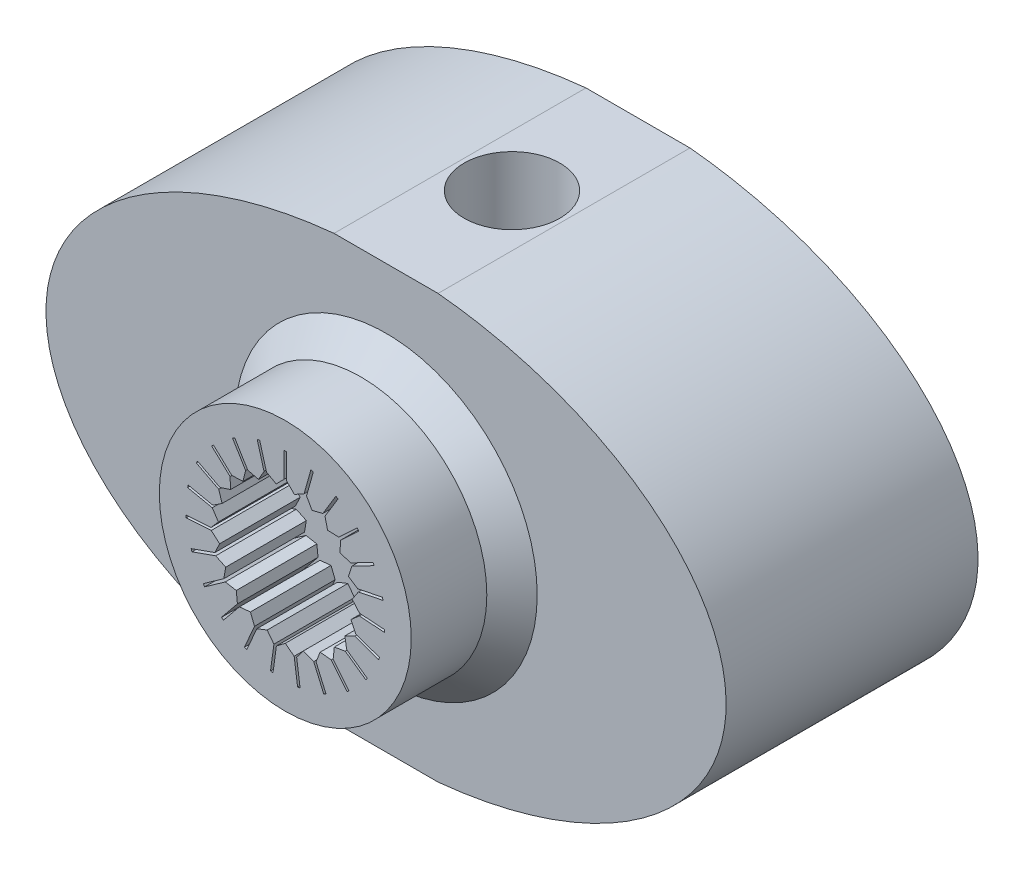
SolidWorks part; units mm, degrees
ref_plane "正面" through (0, 0, 0) normal (0, 0, 1) x (1, 0, 0)
ref_plane "平面" through (0, 0, 0) normal (0, 1, 0) x (1, 0, 0)
ref_plane "右側面" through (0, 0, 0) normal (1, 0, 0) x (0, 0, -1)
sketch "ｽｹｯﾁ1" plane through (0, 0, 0) normal (0, 0, 1) x (1, 0, 0)
  ellipse E0 centre (0, 0) end of major axis (-13.5, 0) minor radius 8.5
  dimension "D1" = 13.5
  dimension "D2" = 8.5
extrude "ﾎﾞｽ - 押し出し1" add sketch "ｽｹｯﾁ1" along normal blind 10
sketch "ｽｹｯﾁ2" plane through (0, 0, 0) normal (0, 1, 0) x (1, 0, 0)
  line L1 (2.5, -13.2881) -> (-2.5, -13.2881)
  line L2 (2.5, -13.2881) -> (2.5, 3.6993)
  line L3 (2.5, 3.6993) -> (-2.5, 3.6993)
  line L4 (-2.5, -13.2881) -> (-2.5, 3.6993)
  line L5 (2.5, -13.2881) -> (-2.5, 3.6993) construction
  line L6 (2.5, 3.6993) -> (-2.5, -13.2881) construction
  point P0 (0, -4.7944)
  dimension "D1" = 5
extrude "ｶｯﾄ - 押し出し2" cut sketch "ｽｹｯﾁ2" against normal blind 10 from offset 18.4
mirror "ﾐﾗｰ1" about plane through (0, 0, 0) normal (0, 1, 0) of "ｶｯﾄ - 押し出し2"
sketch "ｽｹｯﾁ3" plane through (0, 8.4, 0) normal (0, 1, 0) x (1, 0, 0)
  line L0 (2.0647, 0) -> (-2.0647, 0) construction
  line L1 (-2.0647, 0) -> (-2.0647, -10) construction
  circle A0 centre (0, -5) radius 1.9
  point P4 (0, 0)
  point P7 (-2.0647, -5)
  dimension "D1" = 3.8
extrude "ｶｯﾄ - 押し出し3" cut sketch "ｽｹｯﾁ3" against normal through all both and the other way through all
sketch "ｽｹｯﾁ6" plane through (0, 0, 10) normal (0, 0, 1) x (1, 0, 0)
  circle A0 centre (0, 0) radius 5
  dimension "D1" = 10
extrude "ﾎﾞｽ - 押し出し3" add sketch "ｽｹｯﾁ6" along normal blind 4
sketch "ｽｹｯﾁ5" plane through (0, 0, 14) normal (0, 0, 1) x (1, 0, 0)
  line L0 (-0.3625, 2.6375) -> (0, 3) construction
  line L1 (0, 3) -> (0.3625, 2.6375) construction
  line L2 (-0.3625, 2.6375) -> (0, 0) construction
  line L3 (0, 0) -> (0.3625, 2.6375) construction
  line L4 (0, 3) -> (0, 0) construction
  line L5 (-0.05, 2.95) -> (-0.05, 3.95)
  line L6 (-0.05, 3.95) -> (0.05, 3.95)
  line L7 (0.05, 3.95) -> (0.05, 2.95)
  line L8 (-0.05, 2.95) -> (0.05, 2.95) construction
  line L9 (-0.3625, 2.6375) -> (-0.05, 2.95)
  line L10 (-0.05, 2.95) -> (0.05, 2.95) construction
  line L11 (0.3625, 2.6375) -> (0.05, 2.95)
  line L12 (0.3625, 2.6375) -> (0.7478, 2.8541)
  line L13 (0.7478, 2.8541) -> (1.0176, 3.817)
  line L14 (1.1138, 3.79) -> (0.844, 2.8271)
  line L15 (1.0607, 2.4419) -> (0.844, 2.8271)
  line L16 (1.0176, 3.817) -> (1.1138, 3.79)
  line L17 (1.0607, 2.4419) -> (1.4901, 2.5465)
  line L18 (1.4901, 2.5465) -> (2.0096, 3.4009)
  line L19 (2.0951, 3.349) -> (1.5755, 2.4946)
  line L20 (1.6801, 2.0652) -> (1.5755, 2.4946)
  line L21 (2.0096, 3.4009) -> (2.0951, 3.349)
  line L22 (1.6801, 2.0652) -> (2.1218, 2.0501)
  line L23 (2.1218, 2.0501) -> (2.8527, 2.7326)
  line L24 (2.9209, 2.6595) -> (2.1901, 1.977)
  line L25 (2.175, 1.5353) -> (2.1901, 1.977)
  line L26 (2.8527, 2.7326) -> (2.9209, 2.6595)
  line L27 (2.175, 1.5353) -> (2.5963, 1.4016)
  line L28 (2.5963, 1.4016) -> (3.4841, 1.8617)
  line L29 (3.5301, 1.7729) -> (2.6423, 1.3128)
  line L30 (2.5086, 0.8915) -> (2.6423, 1.3128)
  line L31 (3.4841, 1.8617) -> (3.5301, 1.7729)
  line L32 (2.5086, 0.8915) -> (2.8781, 0.6491)
  line L33 (2.8781, 0.6491) -> (3.8572, 0.8526)
  line L34 (3.8776, 0.7547) -> (2.8985, 0.5512)
  line L35 (2.6561, 0.1817) -> (2.8985, 0.5512)
  line L36 (3.8572, 0.8526) -> (3.8776, 0.7547)
  line L37 (2.6561, 0.1817) -> (2.9465, -0.1514)
  line L38 (2.9465, -0.1514) -> (3.9442, -0.2197)
  line L39 (3.9374, -0.3194) -> (2.9397, -0.2512)
  line L40 (2.6066, -0.5417) -> (2.9397, -0.2512)
  line L41 (3.9442, -0.2197) -> (3.9374, -0.3194)
  line L42 (2.6066, -0.5417) -> (2.7964, -0.9408)
  line L43 (2.7964, -0.9408) -> (3.7387, -1.2757)
  line L44 (3.7052, -1.3699) -> (2.7629, -1.035)
  line L45 (2.3638, -1.2248) -> (2.7629, -1.035)
  line L46 (3.7387, -1.2757) -> (3.7052, -1.3699)
  line L47 (2.3638, -1.2248) -> (2.4389, -1.6604)
  line L48 (2.4389, -1.6604) -> (3.2559, -2.237)
  line L49 (3.1982, -2.3187) -> (2.3812, -1.7421)
  line L50 (1.9457, -1.8171) -> (2.3812, -1.7421)
  line L51 (3.2559, -2.237) -> (3.1982, -2.3187)
  line L52 (1.9457, -1.8171) -> (1.9005, -2.2568)
  line L53 (1.9005, -2.2568) -> (2.5316, -3.0325)
  line L54 (2.454, -3.0956) -> (1.8229, -2.3199)
  line L55 (1.3833, -2.2747) -> (1.8229, -2.3199)
  line L56 (2.5316, -3.0325) -> (2.454, -3.0956)
  line L57 (1.3833, -2.2747) -> (1.2211, -2.6859)
  line L58 (1.2211, -2.6859) -> (1.6195, -3.6031)
  line L59 (1.5278, -3.6429) -> (1.1294, -2.7257)
  line L60 (0.7183, -2.5636) -> (1.1294, -2.7257)
  line L61 (1.6195, -3.6031) -> (1.5278, -3.6429)
  line L62 (0.7183, -2.5636) -> (0.4512, -2.9157)
  line L63 (0.4512, -2.9157) -> (0.5874, -3.9064)
  line L64 (0.4883, -3.92) -> (0.3522, -2.9293)
  line L65 (0, -2.6623) -> (0.3522, -2.9293)
  line L66 (0.5874, -3.9064) -> (0.4883, -3.92)
  line L67 (0, -2.6623) -> (-0.3522, -2.9293)
  line L68 (-0.3522, -2.9293) -> (-0.4883, -3.92)
  line L69 (-0.5874, -3.9064) -> (-0.4512, -2.9157)
  line L70 (-0.7183, -2.5636) -> (-0.4512, -2.9157)
  line L71 (-0.4883, -3.92) -> (-0.5874, -3.9064)
  line L72 (-0.7183, -2.5636) -> (-1.1294, -2.7257)
  line L73 (-1.1294, -2.7257) -> (-1.5278, -3.6429)
  line L74 (-1.6195, -3.6031) -> (-1.2211, -2.6859)
  line L75 (-1.3833, -2.2747) -> (-1.2211, -2.6859)
  line L76 (-1.5278, -3.6429) -> (-1.6195, -3.6031)
  line L77 (-1.3833, -2.2747) -> (-1.8229, -2.3199)
  line L78 (-1.8229, -2.3199) -> (-2.454, -3.0956)
  line L79 (-2.5316, -3.0325) -> (-1.9005, -2.2568)
  line L80 (-1.9457, -1.8171) -> (-1.9005, -2.2568)
  line L81 (-2.454, -3.0956) -> (-2.5316, -3.0325)
  line L82 (-1.9457, -1.8171) -> (-2.3812, -1.7421)
  line L83 (-2.3812, -1.7421) -> (-3.1982, -2.3187)
  line L84 (-3.2559, -2.237) -> (-2.4389, -1.6604)
  line L85 (-2.3638, -1.2248) -> (-2.4389, -1.6604)
  line L86 (-3.1982, -2.3187) -> (-3.2559, -2.237)
  line L87 (-2.3638, -1.2248) -> (-2.7629, -1.035)
  line L88 (-2.7629, -1.035) -> (-3.7052, -1.3699)
  line L89 (-3.7387, -1.2757) -> (-2.7964, -0.9408)
  line L90 (-2.6066, -0.5417) -> (-2.7964, -0.9408)
  line L91 (-3.7052, -1.3699) -> (-3.7387, -1.2757)
  line L92 (-2.6066, -0.5417) -> (-2.9397, -0.2512)
  line L93 (-2.9397, -0.2512) -> (-3.9374, -0.3194)
  line L94 (-3.9442, -0.2197) -> (-2.9465, -0.1514)
  line L95 (-2.6561, 0.1817) -> (-2.9465, -0.1514)
  line L96 (-3.9374, -0.3194) -> (-3.9442, -0.2197)
  line L97 (-2.6561, 0.1817) -> (-2.8985, 0.5512)
  line L98 (-2.8985, 0.5512) -> (-3.8776, 0.7547)
  line L99 (-3.8572, 0.8526) -> (-2.8781, 0.6491)
  line L100 (-2.5086, 0.8915) -> (-2.8781, 0.6491)
  line L101 (-3.8776, 0.7547) -> (-3.8572, 0.8526)
  line L102 (-2.5086, 0.8915) -> (-2.6423, 1.3128)
  line L103 (-2.6423, 1.3128) -> (-3.5301, 1.7729)
  line L104 (-3.4841, 1.8617) -> (-2.5963, 1.4016)
  line L105 (-2.175, 1.5353) -> (-2.5963, 1.4016)
  line L106 (-3.5301, 1.7729) -> (-3.4841, 1.8617)
  line L107 (-2.175, 1.5353) -> (-2.1901, 1.977)
  line L108 (-2.1901, 1.977) -> (-2.9209, 2.6595)
  line L109 (-2.8527, 2.7326) -> (-2.1218, 2.0501)
  line L110 (-1.6801, 2.0652) -> (-2.1218, 2.0501)
  line L111 (-2.9209, 2.6595) -> (-2.8527, 2.7326)
  line L112 (-1.6801, 2.0652) -> (-1.5755, 2.4946)
  line L113 (-1.5755, 2.4946) -> (-2.0951, 3.349)
  line L114 (-2.0096, 3.4009) -> (-1.4901, 2.5465)
  line L115 (-1.0607, 2.4419) -> (-1.4901, 2.5465)
  line L116 (-2.0951, 3.349) -> (-2.0096, 3.4009)
  line L117 (-1.0607, 2.4419) -> (-0.844, 2.8271)
  line L118 (-0.844, 2.8271) -> (-1.1138, 3.79)
  line L119 (-1.0176, 3.817) -> (-0.7478, 2.8541)
  line L120 (-0.3625, 2.6375) -> (-0.7478, 2.8541)
  line L121 (-1.1138, 3.79) -> (-1.0176, 3.817)
  circle A0 centre (0, 0) radius 3 construction
  circle A1 centre (0, 0) radius 2.6623 construction
  point P147 (0, 0)
  dimension "D1" = 6
  dimension "D2" = 7.826
  dimension "D3" = 7.826
  dimension "D4" = 0.1
  dimension "D5" = 1
  dimension "D6" = 23
extrude "ｶｯﾄ - 押し出し5" cut sketch "ｽｹｯﾁ5" against normal blind 3.2
chamfer "面取り1" distance 1 angle 45 1 edges at (5, 0, 10)
equation "\"18.4.300mm\"=18.3"
equation "\"D2@ｽｹｯﾁ5\"=360deg/46"
equation "\"D3@ｽｹｯﾁ5\"=\"D2@ｽｹｯﾁ5\""
